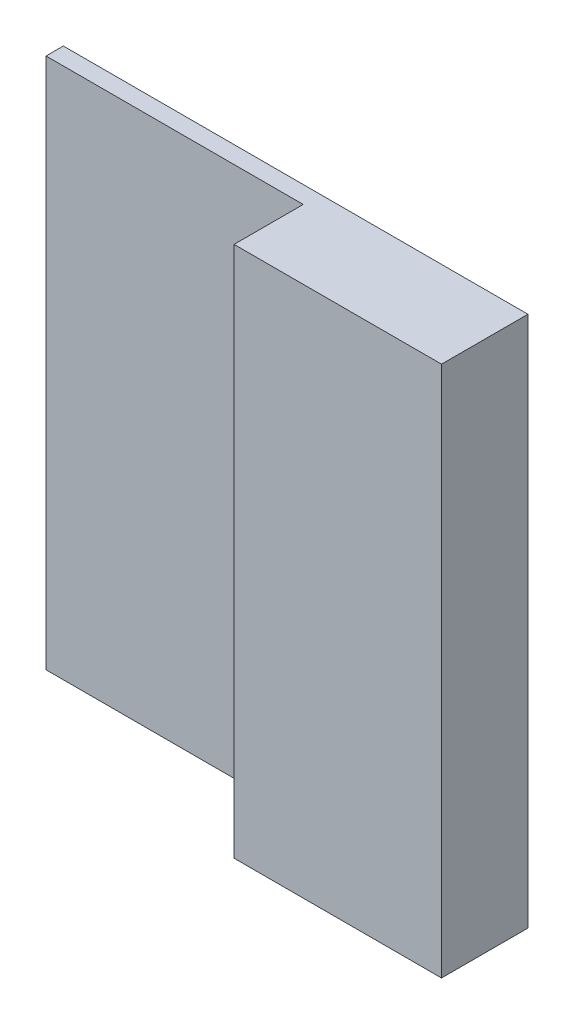
SolidWorks part; units mm, degrees
ref_plane "Front" through (0, 0, 0) normal (0, 0, 1) x (1, 0, 0)
ref_plane "Top" through (0, 0, 0) normal (0, 1, 0) x (1, 0, 0)
ref_plane "Right" through (0, 0, 0) normal (1, 0, 0) x (0, 0, -1)
sketch "Sketch1" plane through (0, 0, 0) normal (0, 1, 0) x (1, 0, 0)
  line L1 (0, 0) -> (-44, 0)
  line L2 (0, 0) -> (0, 4)
  line L3 (0, 4) -> (-44, 4)
  line L4 (-44, 0) -> (-44, 4)
  line L5 (-44, 0) -> (-48, 0)
  line L6 (-44, 0) -> (-44, 20)
  line L7 (-44, 20) -> (-48, 20)
  line L8 (-48, 0) -> (-48, 20)
  line L9 (-44, 20) -> (-107.5, 20)
  line L10 (-44, 20) -> (-44, 16)
  line L11 (-44, 16) -> (-107.5, 16)
  line L12 (-107.5, 20) -> (-107.5, 16)
  line L13 (-44, 20) -> (0, 20)
  line L14 (-44, 20) -> (-44, 4)
  line L15 (-44, 4) -> (0, 4)
  line L16 (0, 20) -> (0, 4)
  dimension "D1" = 4
  dimension "D2" = 44
  dimension "D3" = 4
  dimension "D4" = 20
  dimension "D5" = 4
  dimension "D6" = 63.5
extrude "Boss-Extrude1" add sketch "Sketch1" along normal blind 123 contours L9 L12 L11 L8 | L11 L6 L7 L8 | L6 L11 L8 L5 L4 | L4 L1 L2 L3 | L16 L13 L6 L3
